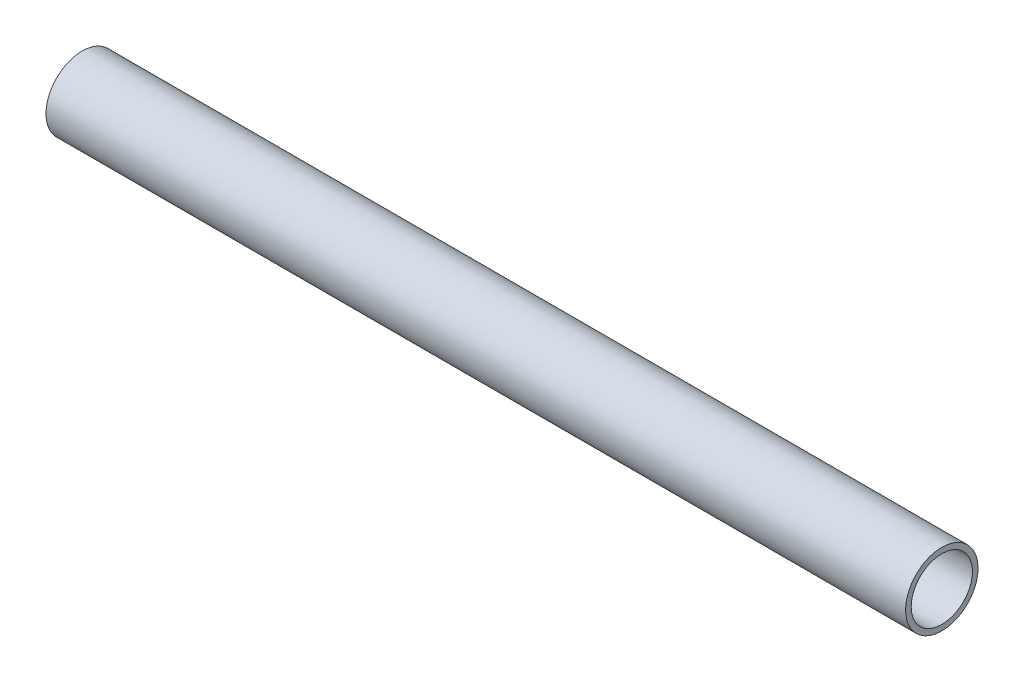
SolidWorks part; units mm, degrees
ref_plane "Front Plane" through (0, 0, 0) normal (0, 0, 1) x (1, 0, 0)
ref_plane "Top Plane" through (0, 0, 0) normal (0, 1, 0) x (1, 0, 0)
ref_plane "Right Plane" through (0, 0, 0) normal (1, 0, 0) x (0, 0, -1)
sketch "Sketch1" plane through (0, 0, 0) normal (1, 0, 0) x (0, 0, -1)
  circle A0 centre (0, 0) radius 5.9055
  circle A1 centre (0, 0) radius 4.9911
  dimension "D1" = 9.9822
  dimension "D2" = 11.811
extrude "Boss-Extrude1" add sketch "Sketch1" along normal mid plane 140.081
scale "Scale1" scale about centroid uniform scaling yes scale factor 0.6
